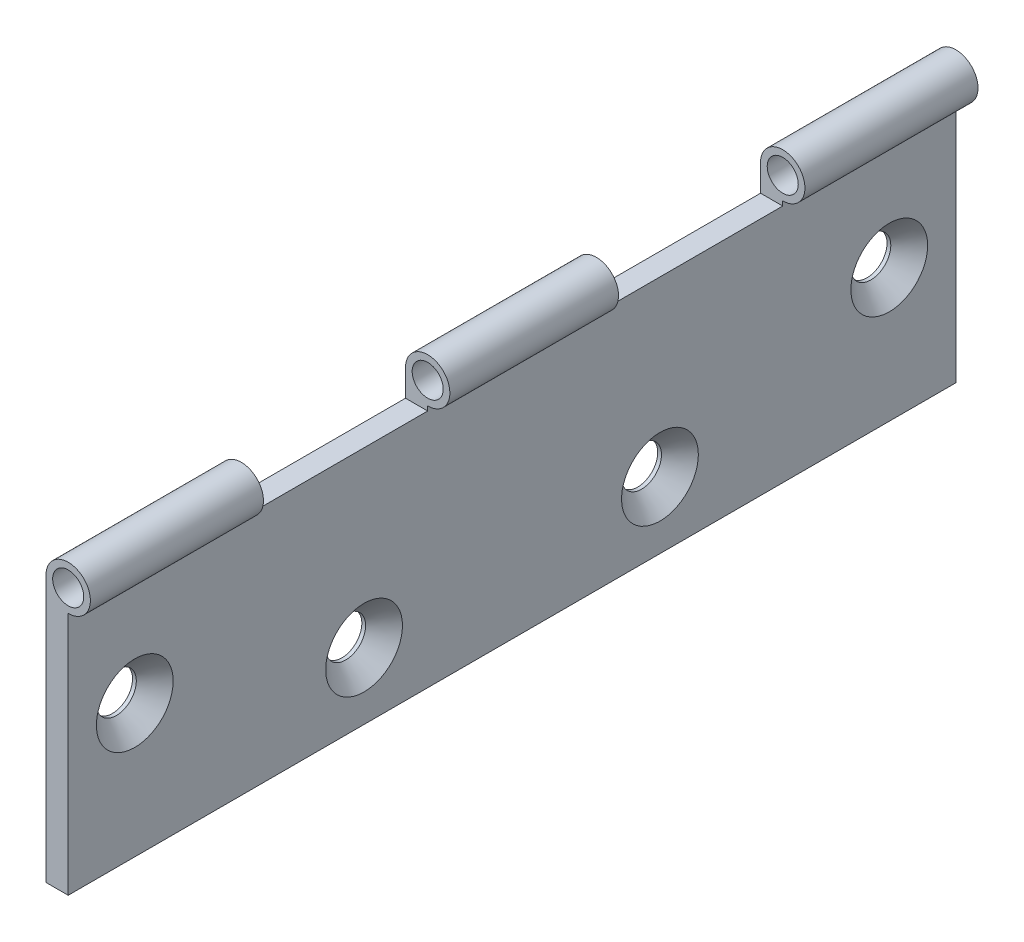
SolidWorks part; units mm, degrees
ref_plane "Front Plane" through (0, 0, 0) normal (0, 0, 1) x (1, 0, 0)
ref_plane "Top Plane" through (0, 0, 0) normal (0, 1, 0) x (1, 0, 0)
ref_plane "Right Plane" through (0, 0, 0) normal (1, 0, 0) x (0, 0, -1)
sketch "Sketch1" plane through (0, 0, 0) normal (0, 0, 1) x (1, 0, 0)
  line L0 (0, 0) -> (0, 60)
  dimension "D1" = 60
extrude "Extrude-Thin1" add sketch "Sketch1" along normal mid plane 200 thin
sketch "Sketch3" plane through (0, 0, 100) normal (0, 0, 1) x (1, 0, 0)
  circle A0 centre (5, 60) radius 5
sweep "Sweep5" add profiles "Sketch3" path edge at (5, 60, 0)
sketch "Sketch13" plane through (0, 0, 100) normal (0, 0, 1) x (1, 0, 0)
  circle A0 centre (5, 60) radius 3.5
  arc A1 (5, 55) -> (0, 60) centre (5, 60) ccw construction
  dimension "D1" = 7
extrude "Cut-Extrude1" cut sketch "Sketch13" against normal through all
hole_wizard "CSK for M8 Flat Head Machine Screw1" positions "Sketch14" profile "Sketch15" countersink size "M8" standard "ANSI Metric" end condition through all
sketch "Sketch14" plane through (5, 0, 0) normal (1, 0, 0) x (0, 0, -1)
  line L0 (-100, 0) -> (-100, 55) construction
  line L1 (-100, 0) -> (100, 0) construction
  point P0 (-85, 30)
  point P2 (-33.3333, 15)
  dimension "D1" = 15
  dimension "D2" = 30
  dimension "D3" = 66.6667
  dimension "D4" = 15
sketch "Sketch15" plane through (5, 30, 85) normal (0, 1, 0) x (0, 0, -1)
  line L0 (0, 0) -> (0, 5)
  line L1 (0, 5) -> (4.5, 5)
  line L2 (4.5, 5) -> (4.5, 4.15)
  line L3 (4.5, 4.15) -> (8.65, 0)
  line L5 (8.65, 0) -> (0, 0)
  line L6 (-4.5, 4.15) -> (-8.65, 0) construction
  line L11 (0, -6.35) -> (0, 107.95) construction
  dimension "Thru Hole Dia." = 9
  dimension "Thru Hole Depth" = 5
  dimension "Near C'Sink Dia." = 17.3
  dimension "Near C'Sink Angle" = 90
mirror "Mirror1" about plane through (0, 0, 0) normal (0, 0, 1) of "CSK for M8 Flat Head Machine Screw1"
sketch "layout for cuts" plane through (5, 0, 0) normal (1, 0, 0) x (0, 0, -1)
  line L1 (100, 55) -> (100, 65) construction
  line L2 (-100, 54) -> (100, 54)
  line L3 (-100, 54) -> (100, 54)
  line L4 (-100, 65) -> (-100, 55) construction
  line L5 (100, 54) -> (100, 65)
  line L6 (-100, 65) -> (-100, 54)
  line L7 (-100, 65) -> (100, 65)
  line L8 (-60, 54) -> (-60, 65)
  line L9 (-20, 54) -> (-20, 65)
  line L10 (0, 0) -> (0, 87.9009) construction
  line L11 (20, 54) -> (20, 65)
  line L12 (60, 54) -> (60, 65)
  point P10 (-60, 59.5)
  dimension "D2" = 40
  dimension "D3" = 40
  dimension "D1" = 1
sketch "Sketch23" plane through (5, 0, 0) normal (1, 0, 0) x (0, 0, -1)
  line L0 (-100, 54) -> (100, 54) construction
  line L1 (100, 54) -> (100, 65) construction
  line L2 (-100, 65) -> (100, 65) construction
  line L3 (-100, 65) -> (-100, 54) construction
  line L4 (100, 55) -> (-100, 55)
  line L5 (-100, 55) -> (-100, 0)
  line L6 (-100, 0) -> (100, 0)
  line L7 (100, 0) -> (100, 55)
  line L8 (100, 55) -> (-100, 55)
  line L9 (-100, 55) -> (-100, 0)
  line L10 (-100, 0) -> (100, 0)
  line L11 (100, 0) -> (100, 55)
  line L12 (-61, 54) -> (-19, 54)
  line L13 (100, 54) -> (100, 65)
  line L14 (-61, 65) -> (-19, 65)
  line L15 (-100, 65) -> (-100, 54)
  line L18 (61, 54) -> (61, 65)
  line L19 (61, 54) -> (61, 65)
  line L21 (-61, 54) -> (-61, 65)
  line L22 (-61, 54) -> (-61, 65)
  line L24 (-19, 54) -> (-19, 65)
  line L25 (-19, 54) -> (-19, 65)
  line L26 (19, 65) -> (61, 65)
  line L27 (19, 54) -> (19, 65)
  line L28 (19, 54) -> (19, 65)
  line L29 (19, 54) -> (61, 54)
  dimension "D1" = 0
  dimension "D2" = 1
  dimension "D3" = 1
  dimension "D4" = 1
  dimension "D5" = 1
extrude "2Cuts" cut sketch "Sketch23" against normal through all and the other way through all contours L14 L25 L12 L22 | L26 L19 L29 L28
sketch "Sketch21" plane through (5, 0, 0) normal (1, 0, 0) x (0, 0, -1)
  line L0 (-100, 54) -> (100, 54) construction
  line L1 (100, 54) -> (100, 65) construction
  line L2 (-100, 65) -> (100, 65) construction
  line L3 (-100, 65) -> (-100, 54) construction
  line L4 (100, 55) -> (61, 55)
  line L5 (-100, 55) -> (-100, 0)
  line L6 (-100, 0) -> (100, 0)
  line L7 (100, 0) -> (100, 55)
  line L8 (100, 55) -> (61, 55)
  line L9 (-100, 55) -> (-100, 0)
  line L10 (-100, 0) -> (100, 0)
  line L11 (100, 0) -> (100, 55)
  line L12 (-100, 54) -> (-59, 54)
  line L13 (100, 54) -> (100, 65)
  line L14 (-100, 65) -> (-59, 65)
  line L15 (-100, 65) -> (-100, 54)
  line L22 (-59, 54) -> (-59, 65)
  line L23 (-59, 54) -> (-59, 65)
  line L25 (59, 54) -> (59, 65)
  line L26 (59, 54) -> (59, 65)
  line L28 (21, 54) -> (21, 65)
  line L29 (21, 54) -> (21, 65)
  line L30 (-21, 54) -> (21, 54)
  line L31 (-21, 54) -> (-21, 65)
  line L32 (-21, 54) -> (-21, 65)
  line L33 (-21, 65) -> (21, 65)
  line L34 (59, 54) -> (100, 54)
  line L35 (59, 65) -> (100, 65)
  line L40 (-61, 54) -> (-61, 55)
  line L41 (-61, 54) -> (-61, 55)
  line L42 (-61, 55) -> (-100, 55)
  line L43 (-61, 55) -> (-100, 55)
  line L44 (61, 55) -> (61, 54)
  line L45 (61, 55) -> (61, 54)
  line L46 (61, 54) -> (19, 54)
  line L47 (61, 54) -> (19, 54)
  line L48 (19, 54) -> (19, 55)
  line L49 (19, 54) -> (19, 55)
  line L50 (19, 55) -> (-19, 55)
  line L51 (19, 55) -> (-19, 55)
  line L52 (-19, 55) -> (-19, 54)
  line L53 (-19, 55) -> (-19, 54)
  line L54 (-19, 54) -> (-61, 54)
  line L55 (-19, 54) -> (-61, 54)
  dimension "D1" = 0
  dimension "D2" = 1
  dimension "D3" = 1
  dimension "D4" = 1
  dimension "D5" = 1
extrude "3Cuts" [suppressed] cut sketch "Sketch21" against normal through all and the other way through all contours L23 L14 L15 L12 | L29 L33 L32 L30 | L13 L35 L26 L34
equation "\"D2@Sketch14\"= \"D1@Sketch1\" / 2"
equation "\"D3@Sketch14\"= \"D1@Extrude-Thin1\" / 3"
equation "\"D2@layout for cuts\"= \"D1@Extrude-Thin1\"/5"
equation "\"D3@layout for cuts\"= \"D1@Extrude-Thin1\" / 5"
